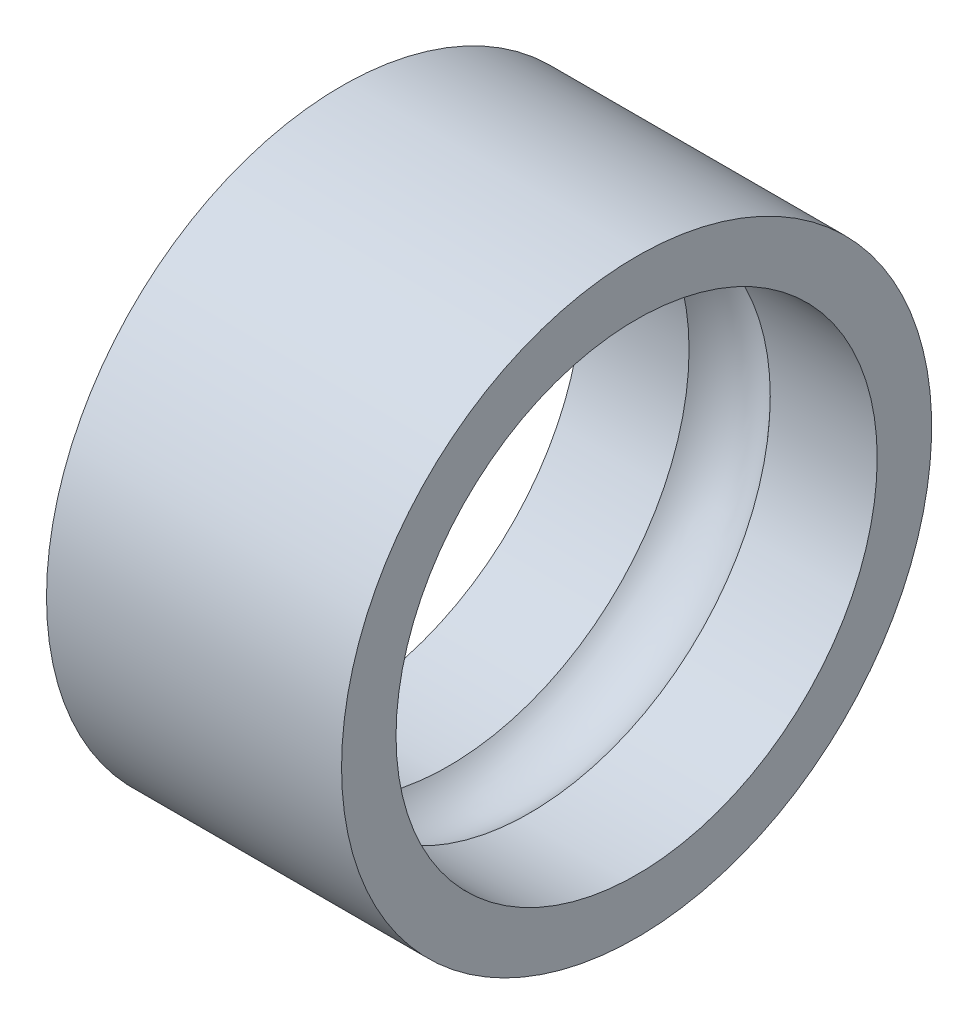
SolidWorks part; units mm, degrees
ref_plane "Front Plane" through (0, 0, 0) normal (0, 0, 1) x (1, 0, 0)
ref_plane "Top Plane" through (0, 0, 0) normal (0, 1, 0) x (1, 0, 0)
ref_plane "Right Plane" through (0, 0, 0) normal (1, 0, 0) x (0, 0, -1)
sketch "Sketch1" plane through (0, 0, 0) normal (0, 0, 1) x (1, 0, 0)
  line L0 (0, 0) -> (17146.0699, 0) construction
  line L1 (2.7521, 16.3077) -> (10, 16.3077)
  line L2 (-10, 20) -> (10, 20)
  line L3 (-10, 20) -> (-10, 16.3077)
  line L4 (-10, 16.3077) -> (-2.7521, 16.3077)
  line L5 (10, 20) -> (10, 16.3077)
  line L6 (-10, 20) -> (10, 16.3077) construction
  line L7 (-10, 16.3077) -> (10, 20) construction
  arc A0 (2.7521, 16.3077) -> (-2.7521, 16.3077) centre (0, 13.8462) ccw
  point P3 (0, 18.1538)
  dimension "D4" = 7.3846
  dimension "D5" = 2.4615
  dimension "D1" = 20
  dimension "D2" = 16.3077
  dimension "D3" = 20
revolve "Revolve1" add sketch "Sketch1" angle 360 about L0
